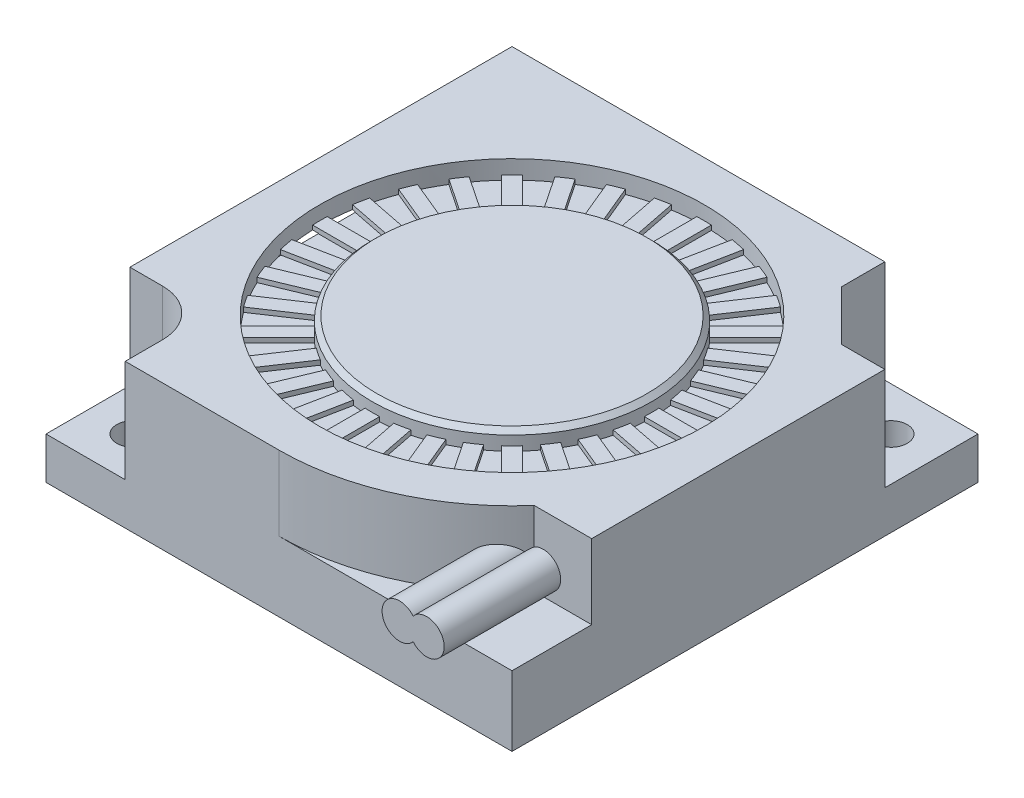
SolidWorks part; units mm, degrees
ref_plane "前视基准面" through (0, 0, 0) normal (0, 0, 1) x (1, 0, 0)
ref_plane "上视基准面" through (0, 0, 0) normal (0, 1, 0) x (1, 0, 0)
ref_plane "右视基准面" through (0, 0, 0) normal (1, 0, 0) x (0, 0, -1)
other "Configuration Table"
sketch "草图1" plane through (0, 0, 0) normal (0, 1, 0) x (1, 0, 0)
  line L1 (-10, 10) -> (10, 10)
  line L2 (-10, 10) -> (-10, -10)
  line L3 (-10, -10) -> (10, -10)
  line L4 (10, 10) -> (10, -10)
  line L5 (-10, 10) -> (10, -10) construction
  line L6 (-10, -10) -> (10, 10) construction
  point P0 (0, 0)
  dimension "D1" = 20
  dimension "D2" = 20
extrude "凸台-拉伸1" add sketch "草图1" along normal blind 6.2
sketch "草图2" plane through (0, 6.2, 0) normal (0, 1, 0) x (1, 0, 0)
  line L0 (-8.1317, -8.1317) -> (8.1317, 8.1317) construction
  line L1 (-10, -10) -> (10, -10) construction
  circle A0 centre (-8.1317, -8.1317) radius 0.7
  circle A1 centre (8.1317, 8.1317) radius 0.7
  dimension "D3" = 1.4
  dimension "D4" = 1.4
  dimension "D1" = 45
  dimension "D2" = 23
extrude "切除-拉伸1" cut sketch "草图2" against normal up to next
sketch "草图3" plane through (0, 6.2, 0) normal (0, 1, 0) x (1, 0, 0)
  line L0 (-8.6, -6.4) -> (-10, -6.4)
  line L1 (-10, 10) -> (-10, -10) construction
  line L2 (-10, -6.4) -> (-10, -10)
  line L3 (-10, -10) -> (-6.6, -10)
  line L4 (-10, -10) -> (10, -10) construction
  line L5 (-6.6, -10) -> (-6.6, -8.4)
  line L6 (6, 8.1317) -> (6, 10)
  line L7 (10, 10) -> (-10, 10) construction
  line L8 (6, 10) -> (10, 10)
  line L9 (10, 10) -> (10, 8.1317)
  line L10 (10, -10) -> (10, 10) construction
  line L11 (10, 8.1317) -> (10, 6)
  line L12 (10, 6) -> (8.1317, 6)
  line L13 (6, 8.1317) -> (8.1317, 6)
  circle A1 centre (8.1317, 8.1317) radius 0.7
  circle A2 centre (8.1317, 8.1317) radius 0.7
  circle A3 centre (-8.1317, -8.1317) radius 0.7
  circle A4 centre (-8.1317, -8.1317) radius 0.7
  arc A6 (-6.6, -8.4) -> (-8.6, -6.4) centre (-8.6, -8.4) ccw
  dimension "D3" = 3.6
  dimension "D4" = 4
  dimension "D5" = 3.4
  dimension "D6" = 2
  dimension "D7" = 4
  dimension "D1" = 0
  dimension "D2" = 0
extrude "切除-拉伸2" cut sketch "草图3" against normal blind 4.4
sketch "草图4" plane through (0, 6.2, 0) normal (0, 1, 0) x (1, 0, 0)
  line L0 (-6.6, -10) -> (10, -10) construction
  line L1 (7.5312, -6.5789) -> (10, -6.5789)
  line L2 (10, -10) -> (10, 6) construction
  line L3 (0, -10) -> (10, -10)
  line L4 (10, -10) -> (10, -6.5789)
  arc A0 (0, -10) -> (7.5312, -6.5789) centre (0, 0) ccw
extrude "切除-拉伸3" cut sketch "草图4" against normal blind 3.2
sketch "草图5" plane through (0, 6.2, 0) normal (0, 1, 0) x (1, 0, 0)
  line L0 (-0.3135, 5.9918) -> (-0.3135, 8.244)
  line L1 (0, 12.5501) -> (0, -15.2229) construction
  line L2 (0.3135, 5.9918) -> (0.3135, 8.244)
  circle A0 centre (0, 0) radius 6
  circle A1 centre (0, 0) radius 8.25
  dimension "D1" = 12
  dimension "D2" = 16.5
extrude "切除-拉伸4" cut sketch "草图5" against normal blind 0.8 contours A0 L1 A1 L2 | A1 L1 A0 L2 | L1 A1 L0 A0 | L1 A0 L0 A1
sketch "草图6" plane through (0, 5.4, 0) normal (0, 1, 0) x (1, 0, 0)
  line L0 (0.3135, 5.9918) -> (0.3135, 8.244) construction
  line L1 (-0.3135, 5.9918) -> (-0.3135, 8.244) construction
  line L2 (0.3135, 5.9918) -> (0.3135, 8.244)
  line L3 (-0.3135, 5.9918) -> (-0.3135, 8.244)
  line L4 (1.4764, 5.8155) -> (1.9158, 8.0245)
  line L5 (0.8615, 5.9378) -> (1.3008, 8.1468)
  line L6 (2.5826, 5.4157) -> (3.4445, 7.4965)
  line L7 (2.0033, 5.6557) -> (2.8652, 7.7365)
  line L8 (3.5895, 4.8078) -> (4.8408, 6.6805)
  line L9 (3.0682, 5.1562) -> (4.3195, 7.0288)
  line L10 (4.4585, 4.0152) -> (6.0511, 5.6077)
  line L11 (4.0152, 4.4585) -> (5.6077, 6.0511)
  line L12 (5.1562, 3.0682) -> (7.0288, 4.3195)
  line L13 (4.8078, 3.5895) -> (6.6805, 4.8408)
  line L14 (5.6557, 2.0033) -> (7.7365, 2.8652)
  line L15 (5.4157, 2.5826) -> (7.4965, 3.4445)
  line L16 (5.9378, 0.8615) -> (8.1468, 1.3008)
  line L17 (5.8155, 1.4764) -> (8.0245, 1.9158)
  line L18 (5.9918, -0.3135) -> (8.244, -0.3135)
  line L19 (5.9918, 0.3135) -> (8.244, 0.3135)
  line L20 (5.8155, -1.4764) -> (8.0245, -1.9158)
  line L21 (5.9378, -0.8615) -> (8.1468, -1.3008)
  line L22 (5.4157, -2.5826) -> (7.4965, -3.4445)
  line L23 (5.6557, -2.0033) -> (7.7365, -2.8652)
  line L24 (4.8078, -3.5895) -> (6.6805, -4.8408)
  line L25 (5.1562, -3.0682) -> (7.0288, -4.3195)
  line L26 (4.0152, -4.4585) -> (5.6077, -6.0511)
  line L27 (4.4585, -4.0152) -> (6.0511, -5.6077)
  line L28 (3.0682, -5.1562) -> (4.3195, -7.0288)
  line L29 (3.5895, -4.8078) -> (4.8408, -6.6805)
  line L30 (2.0033, -5.6557) -> (2.8652, -7.7365)
  line L31 (2.5826, -5.4157) -> (3.4445, -7.4965)
  line L32 (0.8615, -5.9378) -> (1.3008, -8.1468)
  line L33 (1.4764, -5.8155) -> (1.9158, -8.0245)
  line L34 (-0.3135, -5.9918) -> (-0.3135, -8.244)
  line L35 (0.3135, -5.9918) -> (0.3135, -8.244)
  line L36 (-1.4764, -5.8155) -> (-1.9158, -8.0245)
  line L37 (-0.8615, -5.9378) -> (-1.3008, -8.1468)
  line L38 (-2.5826, -5.4157) -> (-3.4445, -7.4965)
  line L39 (-2.0033, -5.6557) -> (-2.8652, -7.7365)
  line L40 (-3.5895, -4.8078) -> (-4.8408, -6.6805)
  line L41 (-3.0682, -5.1562) -> (-4.3195, -7.0288)
  line L42 (-4.4585, -4.0152) -> (-6.0511, -5.6077)
  line L43 (-4.0152, -4.4585) -> (-5.6077, -6.0511)
  line L44 (-5.1562, -3.0682) -> (-7.0288, -4.3195)
  line L45 (-4.8078, -3.5895) -> (-6.6805, -4.8408)
  line L46 (-5.6557, -2.0033) -> (-7.7365, -2.8652)
  line L47 (-5.4157, -2.5826) -> (-7.4965, -3.4445)
  line L48 (-5.9378, -0.8615) -> (-8.1468, -1.3008)
  line L49 (-5.8155, -1.4764) -> (-8.0245, -1.9158)
  line L50 (-5.9918, 0.3135) -> (-8.244, 0.3135)
  line L51 (-5.9918, -0.3135) -> (-8.244, -0.3135)
  line L52 (-5.8155, 1.4764) -> (-8.0245, 1.9158)
  line L53 (-5.9378, 0.8615) -> (-8.1468, 1.3008)
  line L54 (-5.4157, 2.5826) -> (-7.4965, 3.4445)
  line L55 (-5.6557, 2.0033) -> (-7.7365, 2.8652)
  line L56 (-4.8078, 3.5895) -> (-6.6805, 4.8408)
  line L57 (-5.1562, 3.0682) -> (-7.0288, 4.3195)
  line L58 (-4.0152, 4.4585) -> (-5.6077, 6.0511)
  line L59 (-4.4585, 4.0152) -> (-6.0511, 5.6077)
  line L60 (-3.0682, 5.1562) -> (-4.3195, 7.0288)
  line L61 (-3.5895, 4.8078) -> (-4.8408, 6.6805)
  line L62 (-2.0033, 5.6557) -> (-2.8652, 7.7365)
  line L63 (-2.5826, 5.4157) -> (-3.4445, 7.4965)
  line L64 (-0.8615, 5.9378) -> (-1.3008, 8.1468)
  line L65 (-1.4764, 5.8155) -> (-1.9158, 8.0245)
  arc A0 (1.9158, 8.0245) -> (1.3008, 8.1468) centre (0, 0) ccw
  circle A1 centre (0, 0) radius 8.25
  arc A2 (0.3135, 8.244) -> (-0.3135, 8.244) centre (0, 0) ccw
  circle A3 centre (0, 0) radius 6
  arc A4 (0.3135, 5.9918) -> (-0.3135, 5.9918) centre (0, 0) ccw
  arc A5 (1.4764, 5.8155) -> (0.8615, 5.9378) centre (0, 0) ccw
  arc A6 (3.4445, 7.4965) -> (2.8652, 7.7365) centre (0, 0) ccw
  arc A7 (2.5826, 5.4157) -> (2.0033, 5.6557) centre (0, 0) ccw
  arc A8 (4.8408, 6.6805) -> (4.3195, 7.0288) centre (0, 0) ccw
  arc A9 (3.5895, 4.8078) -> (3.0682, 5.1562) centre (0, 0) ccw
  arc A10 (6.0511, 5.6077) -> (5.6077, 6.0511) centre (0, 0) ccw
  arc A11 (4.4585, 4.0152) -> (4.0152, 4.4585) centre (0, 0) ccw
  arc A12 (7.0288, 4.3195) -> (6.6805, 4.8408) centre (0, 0) ccw
  arc A13 (5.1562, 3.0682) -> (4.8078, 3.5895) centre (0, 0) ccw
  arc A14 (7.7365, 2.8652) -> (7.4965, 3.4445) centre (0, 0) ccw
  arc A15 (5.6557, 2.0033) -> (5.4157, 2.5826) centre (0, 0) ccw
  arc A16 (8.1468, 1.3008) -> (8.0245, 1.9158) centre (0, 0) ccw
  arc A17 (5.9378, 0.8615) -> (5.8155, 1.4764) centre (0, 0) ccw
  arc A18 (8.244, -0.3135) -> (8.244, 0.3135) centre (0, 0) ccw
  arc A19 (5.9918, -0.3135) -> (5.9918, 0.3135) centre (0, 0) ccw
  arc A20 (8.0245, -1.9158) -> (8.1468, -1.3008) centre (0, 0) ccw
  arc A21 (5.8155, -1.4764) -> (5.9378, -0.8615) centre (0, 0) ccw
  arc A22 (7.4965, -3.4445) -> (7.7365, -2.8652) centre (0, 0) ccw
  arc A23 (5.4157, -2.5826) -> (5.6557, -2.0033) centre (0, 0) ccw
  arc A24 (6.6805, -4.8408) -> (7.0288, -4.3195) centre (0, 0) ccw
  arc A25 (4.8078, -3.5895) -> (5.1562, -3.0682) centre (0, 0) ccw
  arc A26 (5.6077, -6.0511) -> (6.0511, -5.6077) centre (0, 0) ccw
  arc A27 (4.0152, -4.4585) -> (4.4585, -4.0152) centre (0, 0) ccw
  arc A28 (4.3195, -7.0288) -> (4.8408, -6.6805) centre (0, 0) ccw
  arc A29 (3.0682, -5.1562) -> (3.5895, -4.8078) centre (0, 0) ccw
  arc A30 (2.8652, -7.7365) -> (3.4445, -7.4965) centre (0, 0) ccw
  arc A31 (2.0033, -5.6557) -> (2.5826, -5.4157) centre (0, 0) ccw
  arc A32 (1.3008, -8.1468) -> (1.9158, -8.0245) centre (0, 0) ccw
  arc A33 (0.8615, -5.9378) -> (1.4764, -5.8155) centre (0, 0) ccw
  arc A34 (-0.3135, -8.244) -> (0.3135, -8.244) centre (0, 0) ccw
  arc A35 (-0.3135, -5.9918) -> (0.3135, -5.9918) centre (0, 0) ccw
  arc A36 (-1.9158, -8.0245) -> (-1.3008, -8.1468) centre (0, 0) ccw
  arc A37 (-1.4764, -5.8155) -> (-0.8615, -5.9378) centre (0, 0) ccw
  arc A38 (-3.4445, -7.4965) -> (-2.8652, -7.7365) centre (0, 0) ccw
  arc A39 (-2.5826, -5.4157) -> (-2.0033, -5.6557) centre (0, 0) ccw
  arc A40 (-4.8408, -6.6805) -> (-4.3195, -7.0288) centre (0, 0) ccw
  arc A41 (-3.5895, -4.8078) -> (-3.0682, -5.1562) centre (0, 0) ccw
  arc A42 (-6.0511, -5.6077) -> (-5.6077, -6.0511) centre (0, 0) ccw
  arc A43 (-4.4585, -4.0152) -> (-4.0152, -4.4585) centre (0, 0) ccw
  arc A44 (-7.0288, -4.3195) -> (-6.6805, -4.8408) centre (0, 0) ccw
  arc A45 (-5.1562, -3.0682) -> (-4.8078, -3.5895) centre (0, 0) ccw
  arc A46 (-7.7365, -2.8652) -> (-7.4965, -3.4445) centre (0, 0) ccw
  arc A47 (-5.6557, -2.0033) -> (-5.4157, -2.5826) centre (0, 0) ccw
  arc A48 (-8.1468, -1.3008) -> (-8.0245, -1.9158) centre (0, 0) ccw
  arc A49 (-5.9378, -0.8615) -> (-5.8155, -1.4764) centre (0, 0) ccw
  arc A50 (-8.244, 0.3135) -> (-8.244, -0.3135) centre (0, 0) ccw
  arc A51 (-5.9918, 0.3135) -> (-5.9918, -0.3135) centre (0, 0) ccw
  arc A52 (-8.0245, 1.9158) -> (-8.1468, 1.3008) centre (0, 0) ccw
  arc A53 (-5.8155, 1.4764) -> (-5.9378, 0.8615) centre (0, 0) ccw
  arc A54 (-7.4965, 3.4445) -> (-7.7365, 2.8652) centre (0, 0) ccw
  arc A55 (-5.4157, 2.5826) -> (-5.6557, 2.0033) centre (0, 0) ccw
  arc A56 (-6.6805, 4.8408) -> (-7.0288, 4.3195) centre (0, 0) ccw
  arc A57 (-4.8078, 3.5895) -> (-5.1562, 3.0682) centre (0, 0) ccw
  arc A58 (-5.6077, 6.0511) -> (-6.0511, 5.6077) centre (0, 0) ccw
  arc A59 (-4.0152, 4.4585) -> (-4.4585, 4.0152) centre (0, 0) ccw
  arc A60 (-4.3195, 7.0288) -> (-4.8408, 6.6805) centre (0, 0) ccw
  arc A61 (-3.0682, 5.1562) -> (-3.5895, 4.8078) centre (0, 0) ccw
  arc A62 (-2.8652, 7.7365) -> (-3.4445, 7.4965) centre (0, 0) ccw
  arc A63 (-2.0033, 5.6557) -> (-2.5826, 5.4157) centre (0, 0) ccw
  arc A64 (-1.3008, 8.1468) -> (-1.9158, 8.0245) centre (0, 0) ccw
  arc A65 (-0.8615, 5.9378) -> (-1.4764, 5.8155) centre (0, 0) ccw
  point P135 (0, 0)
  dimension "D3" = 32
  dimension "D1" = 0
  dimension "D2" = 0
extrude "凸台-拉伸2" add sketch "草图6" along normal blind 0.2
chamfer "倒角1" distance 0.2 angle 45 1 edges at (0, 6.2, 6)
sketch "草图7" plane through (-10, 0, 0) normal (-1, 0, 0) x (0, 0, 1)
  line L1 (-9.0385, 5.4168) -> (5.5854, 5.4168)
  line L2 (-9.0385, 5.4168) -> (-9.0385, 0.9013)
  line L3 (-9.0385, 0.9013) -> (5.5854, 0.9013)
  line L4 (5.5854, 5.4168) -> (5.5854, 0.9013)
extrude "切除-拉伸5" cut sketch "草图7" against normal blind 2
sketch "草图8" plane through (0, 0, 6.5789) normal (0, 0, 1) x (1, 0, 0)
  arc A0 (7.3364, 3.5405) -> (7.3364, 4.4861) centre (7.9186, 4.0133) ccw
  arc A1 (7.3364, 4.4861) -> (7.3364, 3.5405) centre (6.7542, 4.0133) ccw
  dimension "D1" = 1.5
  dimension "D2" = 1.5
extrude "凸台-拉伸3" add sketch "草图8" along normal blind 5
